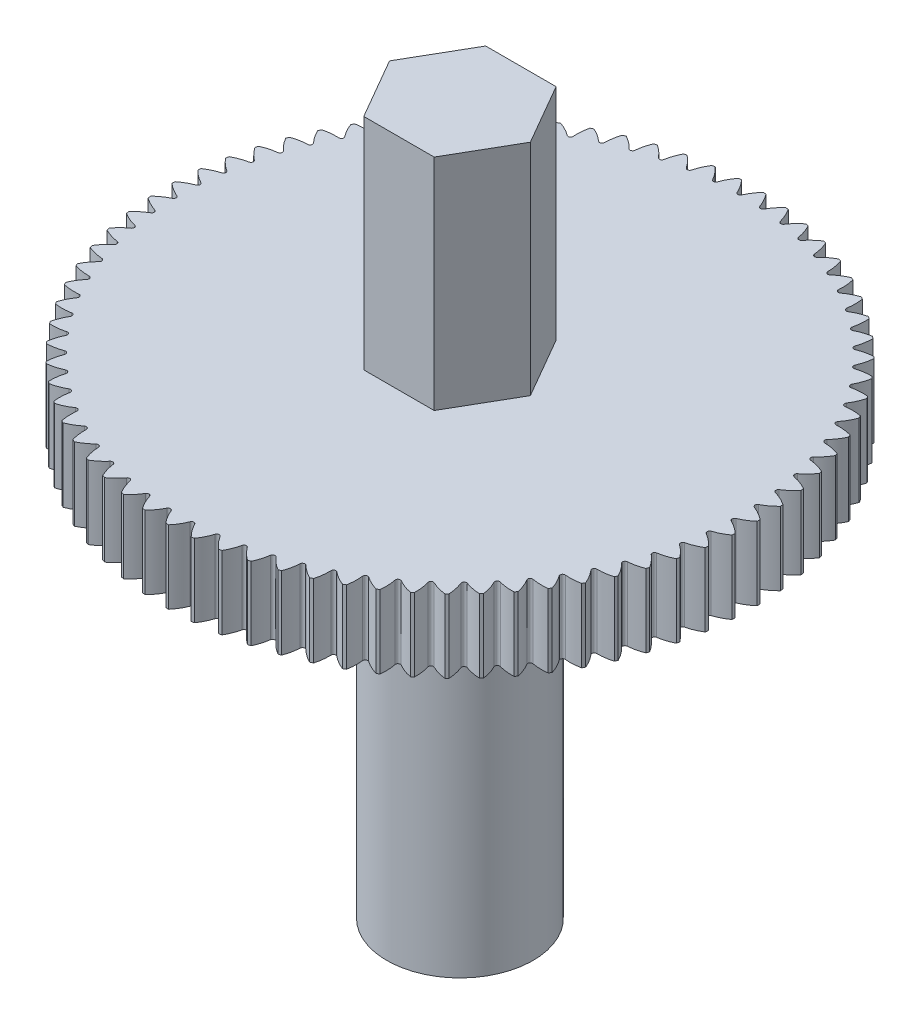
SolidWorks part; units mm, degrees
ref_plane "前视基准面" through (0, 0, 0) normal (0, 0, 1) x (1, 0, 0)
ref_plane "上视基准面" through (0, 0, 0) normal (0, 1, 0) x (1, 0, 0)
ref_plane "右视基准面" through (0, 0, 0) normal (1, 0, 0) x (0, 0, -1)
sketch "草图1" plane through (0, 0, 0) normal (0, 0, 1) x (1, 0, 0)
  line L0 (0, 0) -> (0, 29)
  line L1 (0, 29) -> (3, 29)
  line L2 (3, 29) -> (3, 20)
  line L3 (3, 20) -> (12, 20)
  line L4 (12, 20) -> (12, 17)
  line L5 (12, 17) -> (3, 17)
  line L6 (3, 17) -> (3, 0)
  line L7 (3, 0) -> (0, 0)
  dimension "D1" = 3
  dimension "D2" = 29
  dimension "D3" = 3
  dimension "D4" = 9
  dimension "D5" = 17
revolve "旋转1" add sketch "草图1" angle 360 about L0
sketch "草图2" plane through (0, 20, 0) normal (0, 1, 0) x (1, 0, 0)
  line L0 (0, 0) -> (0, 12) construction
  line L1 (-0.45, 12) -> (0.45, 12)
  circle A0 centre (0, 0) radius 12 construction
  arc A1 (0.45, 12) -> (0.0912, 11.459) centre (1.9153, 10.6388) ccw
  arc A2 (0.0912, 11.459) -> (-0.0912, 11.459) centre (0, 11.5) cw
  arc A3 (-0.45, 12) -> (-0.0912, 11.459) centre (-1.9153, 10.6388) cw
  point P8 (0, 12)
  dimension "D2" = 0.1
  dimension "D3" = 2
  dimension "D1" = 0.9
  dimension "D4" = 0.5
extrude "切除-拉伸1" cut sketch "草图2" against normal blind 10
pattern_circular "阵列(圆周)1" count 75 over 360 about axis through (0, 0, 0) along (0, 1, 0) of "切除-拉伸1"
sketch "草图3" plane through (0, 29, 0) normal (0, 1, 0) x (1, 0, 0)
  line L1 (2.8868, 0) -> (1.4434, 2.5)
  line L2 (1.4434, 2.5) -> (-1.4434, 2.5)
  line L3 (-1.4434, 2.5) -> (-2.8868, 0)
  line L4 (-2.8868, 0) -> (-1.4434, -2.5)
  line L5 (-1.4434, -2.5) -> (1.4434, -2.5)
  line L6 (1.4434, -2.5) -> (2.8868, 0)
  circle A0 centre (0, 0) radius 2.5 construction
  circle A1 centre (0, 0) radius 3 construction
  circle A2 centre (0, 0) radius 3
  dimension "D1" = 5
extrude "切除-拉伸2" cut sketch "草图3" against normal up to surface (9 mm away) up to face at (0, 20, 0)
